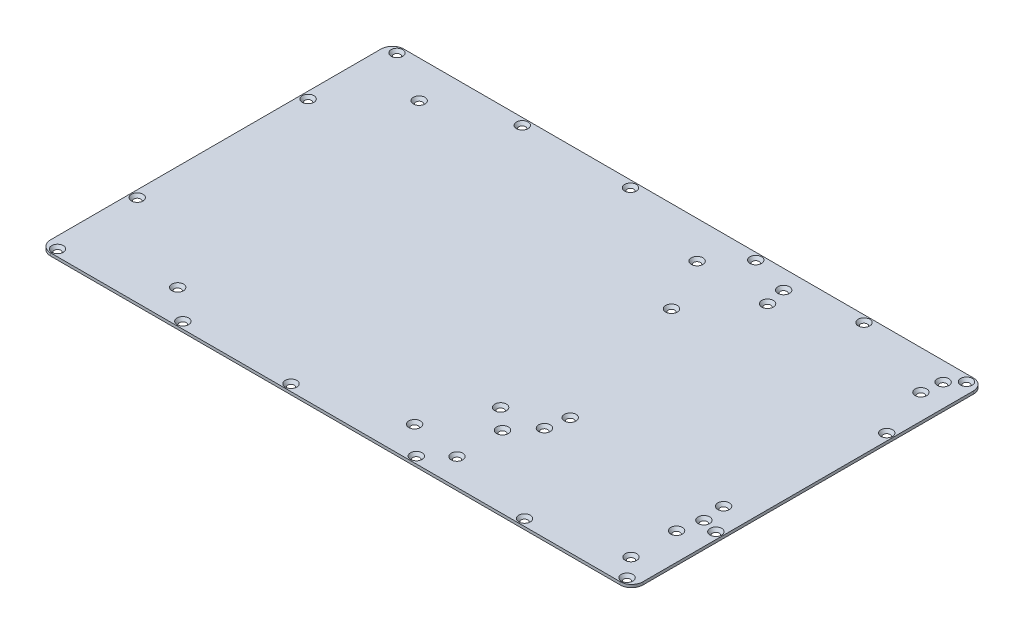
SolidWorks part; units mm, degrees
material "5052-H32"
ref_plane "Front Plane" through (0, 0, 0) normal (0, 0, 1) x (1, 0, 0)
ref_plane "Top Plane" through (0, 0, 0) normal (0, 1, 0) x (1, 0, 0)
ref_plane "Right Plane" through (0, 0, 0) normal (1, 0, 0) x (0, 0, -1)
sketch "Sketch1" plane through (0, 0, 0) normal (0, 1, 0) x (1, 0, 0)
  line L1 (-165.1, -98.425) -> (165.1, -98.425)
  line L2 (-165.1, -98.425) -> (-165.1, 98.425)
  line L3 (-165.1, 98.425) -> (165.1, 98.425)
  line L4 (165.1, -98.425) -> (165.1, 98.425)
  line L5 (-165.1, -98.425) -> (165.1, 98.425) construction
  line L6 (-165.1, 98.425) -> (165.1, -98.425) construction
  point P0 (0, 0)
  dimension "D1" = 330.2
  dimension "D2" = 196.85
extrude "Boss-Extrude1" add sketch "Sketch1" along normal blind 1.5875
fillet "Fillet1" radius 6.35 4 edges at (-165.1, 0.7937, 98.425) (-165.1, 0.7937, -98.425) (165.1, 0.7937, -98.425) (165.1, 0.7937, 98.425)
hole_wizard "CSK for #4 Flat Head Socket Cap Screw1" positions "Sketch3" profile "Sketch2" countersink size "#4" standard "Ansi Inch" end condition through all
sketch "Sketch3" plane through (0, 1.5875, 0) normal (0, 1, 0) x (-1, 0, 0)
  line L0 (-165.1, 92.075) -> (-165.1, -92.075) construction
  line L1 (-158.75, -98.425) -> (158.75, -98.425) construction
  line L2 (158.75, 98.425) -> (-158.75, 98.425) construction
  point P0 (-161.29, 47.625)
  point P1 (-161.29, -47.625)
  dimension "D1" = 3.81
  dimension "D2" = 50.8
  dimension "D3" = 50.8
sketch "Sketch2" plane through (161.29, 1.5875, 47.625) normal (1, 0, 0) x (0, 0, 1)
  line L0 (0, 0) -> (0, 1.5875)
  line L1 (0, 1.5875) -> (1.632, 1.5875)
  line L2 (1.632, 1.5875) -> (1.6319, 1.8481)
  line L3 (1.6319, 1.8481) -> (3.2385, 0)
  line L5 (3.2385, 0) -> (0, 0)
  line L6 (-1.6319, 1.8481) -> (-3.2385, 0) construction
  line L11 (0, -6.35) -> (0, 107.95) construction
  dimension "Thru Hole Dia." = 3.2639
  dimension "Thru Hole Depth" = 1.5875
  dimension "Near C'Sink Dia." = 6.477
  dimension "Near C'Sink Angle" = 82
pattern_linear "LPattern1" count 2 spacing 120.015 along (-1, 0, 0) of "CSK for #4 Flat Head Socket Cap Screw1"
mirror "Mirror1" about plane through (0, 0, 0) normal (1, 0, 0) of "CSK for #4 Flat Head Socket Cap Screw1"
hole_wizard "CSK for #4 Flat Head Socket Cap Screw2" positions "Sketch6" profile "Sketch7" countersink size "#4" standard "Ansi Inch" end condition through all
sketch "Sketch6" plane through (0, 1.5875, 0) normal (0, 1, 0) x (-1, 0, 0)
  line L0 (-171.823, 94.615) -> (176.2442, 94.615) construction
  line L2 (158.75, 98.425) -> (-158.75, 98.425) construction
  line L3 (-165.1, 92.075) -> (-165.1, -92.075) construction
  point P0 (-158.75, 94.615)
  point P7 (-101.6, 94.615)
  point P9 (-41.275, 94.615)
  point P11 (28.575, 94.615)
  point P13 (88.9, 94.615)
  point P15 (158.75, 94.615)
  point P27 (-41.275, 94.615)
  dimension "D1" = 3.81
  dimension "D2" = 6.35
  dimension "D3" = 57.15
  dimension "D4" = 117.475
  dimension "D5" = 69.85
  dimension "D6" = 200.025
  dimension "D7" = 69.85
sketch "Sketch7" plane through (158.75, 1.5875, 94.615) normal (1, 0, 0) x (0, 0, 1)
  line L0 (0, 0) -> (0, 1.5875)
  line L1 (0, 1.5875) -> (1.632, 1.5875)
  line L2 (1.632, 1.5875) -> (1.6319, 1.8481)
  line L3 (1.6319, 1.8481) -> (3.2385, 0)
  line L5 (3.2385, 0) -> (0, 0)
  line L6 (-1.6319, 1.8481) -> (-3.2385, 0) construction
  line L11 (0, -6.35) -> (0, 107.95) construction
  dimension "Thru Hole Dia." = 3.2639
  dimension "Thru Hole Depth" = 1.5875
  dimension "Near C'Sink Dia." = 6.477
  dimension "Near C'Sink Angle" = 82
mirror "Mirror2" about plane through (0, 0, 0) normal (0, 0, 1) of "CSK for #4 Flat Head Socket Cap Screw2"
hole_wizard "CSK for #4 Flat Head Socket Cap Screw3" positions "Sketch10" profile "Sketch9" countersink size "#4" standard "Ansi Inch" end condition through all
sketch "Sketch10" plane through (0, 1.5875, 0) normal (0, 1, 0) x (-1, 0, 0)
  line L0 (-158.75, -98.425) -> (158.75, -98.425) construction
  line L1 (-165.1, 92.075) -> (-165.1, -92.075) construction
  point P0 (-152.4, -87.9348)
  point P1 (-63.5, -87.9348)
  point P3 (-63.5, 45.4152)
  point P5 (-152.4, 45.4152)
  dimension "D1" = 88.9
  dimension "D2" = 133.35
  dimension "D3" = 10.4902
  dimension "D4" = 12.7
sketch "Sketch9" plane through (152.4, 1.5875, -87.9348) normal (1, 0, 0) x (0, 0, 1)
  line L0 (0, 0) -> (0, 1.5875)
  line L1 (0, 1.5875) -> (1.632, 1.5875)
  line L2 (1.632, 1.5875) -> (1.6319, 1.8481)
  line L3 (1.6319, 1.8481) -> (3.2385, 0)
  line L5 (3.2385, 0) -> (0, 0)
  line L6 (-1.6319, 1.8481) -> (-3.2385, 0) construction
  line L11 (0, -6.35) -> (0, 107.95) construction
  dimension "Thru Hole Dia." = 3.2639
  dimension "Thru Hole Depth" = 1.5875
  dimension "Near C'Sink Dia." = 6.477
  dimension "Near C'Sink Angle" = 82
hole_wizard "CSK for #4 Flat Head Socket Cap Screw4" positions "Sketch12" profile "Sketch11" countersink size "#4" standard "Ansi Inch" end condition through all
sketch "Sketch12" plane through (0, 1.5875, 0) normal (0, 1, 0) x (-1, 0, 0)
  line L0 (-158.75, -98.425) -> (158.75, -98.425) construction
  line L1 (-165.1, 92.075) -> (-165.1, -92.075) construction
  point P0 (-65.6336, -76.835)
  point P1 (-151.13, -76.835)
  point P3 (-65.6336, 33.1724)
  point P5 (-151.13, 33.1724)
  dimension "D1" = 21.59
  dimension "D2" = 13.97
  dimension "D3" = 85.4964
  dimension "D4" = 110.0074
sketch "Sketch11" plane through (65.6336, 1.5875, -76.835) normal (1, 0, 0) x (0, 0, 1)
  line L0 (0, 0) -> (0, 1.5875)
  line L1 (0, 1.5875) -> (1.632, 1.5875)
  line L2 (1.632, 1.5875) -> (1.6319, 1.8481)
  line L3 (1.6319, 1.8481) -> (3.2385, 0)
  line L5 (3.2385, 0) -> (0, 0)
  line L6 (-1.6319, 1.8481) -> (-3.2385, 0) construction
  line L11 (0, -6.35) -> (0, 107.95) construction
  dimension "Thru Hole Dia." = 3.2639
  dimension "Thru Hole Depth" = 1.5875
  dimension "Near C'Sink Dia." = 6.477
  dimension "Near C'Sink Angle" = 82
hole_wizard "CSK for #4 Flat Head Socket Cap Screw5" positions "Sketch14" profile "Sketch13" countersink size "#4" standard "Ansi Inch" end condition through all
sketch "Sketch14" plane through (0, 1.5875, 0) normal (0, 1, 0) x (-1, 0, 0)
  line L0 (-165.1, 92.075) -> (-165.1, -92.075) construction
  circle A0 centre (-152.4, 45.4152) radius 1.8585 construction
  point P0 (-149.86, 58.1152)
  point P1 (-149.86, 83.5152)
  point P3 (-52.832, 58.1152)
  point P5 (-52.832, 83.5152)
  dimension "D1" = 12.7
  dimension "D2" = 97.028
  dimension "D3" = 25.4
  dimension "D4" = 15.24
sketch "Sketch13" plane through (149.86, 1.5875, 58.1152) normal (1, 0, 0) x (0, 0, 1)
  line L0 (0, 0) -> (0, 1.5875)
  line L1 (0, 1.5875) -> (1.632, 1.5875)
  line L2 (1.632, 1.5875) -> (1.6319, 1.8481)
  line L3 (1.6319, 1.8481) -> (3.2385, 0)
  line L5 (3.2385, 0) -> (0, 0)
  line L6 (-1.6319, 1.8481) -> (-3.2385, 0) construction
  line L11 (0, -6.35) -> (0, 107.95) construction
  dimension "Thru Hole Dia." = 3.2639
  dimension "Thru Hole Depth" = 1.5875
  dimension "Near C'Sink Dia." = 6.477
  dimension "Near C'Sink Angle" = 82
hole_wizard "CSK for #4 Flat Head Socket Cap Screw6" positions "Sketch16" profile "Sketch15" countersink size "#4" standard "Ansi Inch" end condition through all
sketch "Sketch16" plane through (0, 1.5875, 0) normal (0, 1, 0) x (-1, 0, 0)
  line L0 (165.1, -92.075) -> (165.1, 92.075) construction
  line L1 (-158.75, -98.425) -> (158.75, -98.425) construction
  point P0 (129.54, -77.7748)
  point P1 (-25.4, -77.7748)
  point P3 (-25.4, 79.7052)
  point P5 (106.68, 79.7052)
  dimension "D1" = 35.56
  dimension "D2" = 20.6502
  dimension "D3" = 154.94
  dimension "D4" = 157.48
  dimension "D5" = 132.08
sketch "Sketch15" plane through (-129.54, 1.5875, -77.7748) normal (1, 0, 0) x (0, 0, 1)
  line L0 (0, 0) -> (0, 1.5875)
  line L1 (0, 1.5875) -> (1.632, 1.5875)
  line L2 (1.632, 1.5875) -> (1.6319, 1.8481)
  line L3 (1.6319, 1.8481) -> (3.2385, 0)
  line L5 (3.2385, 0) -> (0, 0)
  line L6 (-1.6319, 1.8481) -> (-3.2385, 0) construction
  line L11 (0, -6.35) -> (0, 107.95) construction
  dimension "Thru Hole Dia." = 3.2639
  dimension "Thru Hole Depth" = 1.5875
  dimension "Near C'Sink Dia." = 6.477
  dimension "Near C'Sink Angle" = 82
